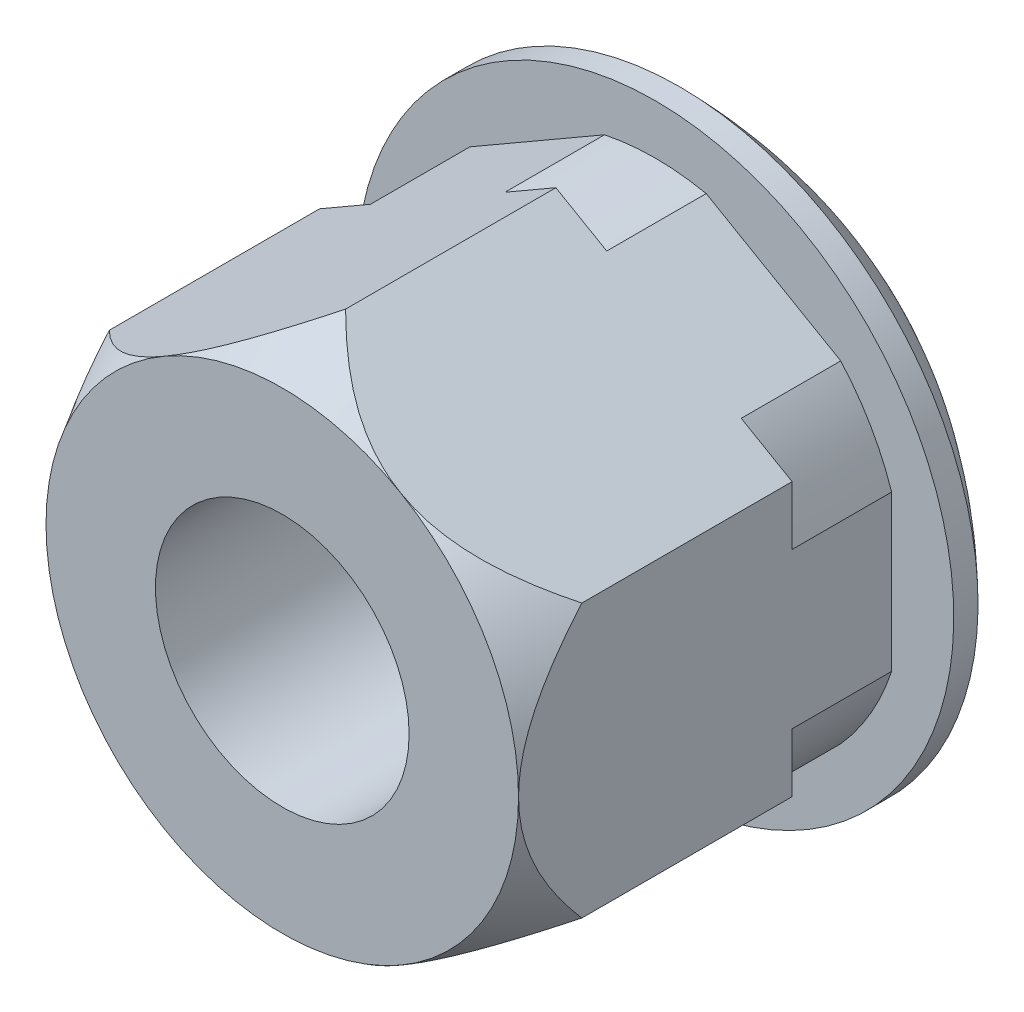
SolidWorks part; units mm, degrees
ref_plane "前视基准面" through (0, 0, 0) normal (0, 0, 1) x (1, 0, 0)
ref_plane "上视基准面" through (0, 0, 0) normal (0, 1, 0) x (1, 0, 0)
ref_plane "右视基准面" through (0, 0, 0) normal (1, 0, 0) x (0, 0, -1)
sketch "草图1" plane through (0, 0, 0) normal (0, 0, 1) x (1, 0, 0)
  line L1 (0, 10.9697) -> (-9.5, 5.4848)
  line L2 (-9.5, 5.4848) -> (-9.5, -5.4848)
  line L3 (-9.5, -5.4848) -> (0, -10.9697)
  line L4 (0, -10.9697) -> (9.5, -5.4848)
  line L5 (9.5, -5.4848) -> (9.5, 5.4848)
  line L6 (9.5, 5.4848) -> (0, 10.9697)
  circle A0 centre (0, 0) radius 9.5 construction
  point P1 (0, 0)
  dimension "D1" = 19
extrude "凸台-拉伸1" add sketch "草图1" against normal blind 15
sketch "草图2" plane through (0, 0, -15) normal (0, 0, -1) x (-1, 0, 0)
  circle A0 centre (0, 0) radius 10
  dimension "D1" = 20
extrude "切除-拉伸1" cut sketch "草图2" against normal blind 4 flip side to cut
sketch "草图3" plane through (0, 0, 0) normal (1, 0, 0) x (0, 0, -1)
  line L0 (15, 0) -> (15, 12)
  line L1 (15, -3.1225) -> (15, 3.1225) construction
  line L2 (15, 12) -> (15.9759, 12)
  line L3 (20, 6.5) -> (20, 0)
  line L4 (8.25, 0) -> (-8.25, 0) construction
  line L5 (20, 0) -> (15, 0) construction
  line L6 (0, 11) -> (0, -11) construction
  line L7 (15, 0) -> (20, 0)
  arc A0 (15.9759, 12) -> (20, 6.5) centre (-2, -5.3743) cw
  point P7 (15.4879, 12)
  point P13 (16.7826, 12)
  dimension "D1" = 25
  dimension "D2" = 24
  dimension "D3" = 13
  dimension "D4" = 20
  dimension "D5" = 5
  dimension "D6" = 2
revolve "旋转1" add sketch "草图3" angle 360 about L5
sketch "草图4" plane through (0, 0, 0) normal (0, 0, 1) x (1, 0, 0)
  circle A0 centre (0, 0) radius 9.5
  dimension "D1" = 19
extrude "切除-拉伸2" cut sketch "草图4" against normal through all draft 30 flip side to cut
hole_wizard "M12 螺纹孔1" positions "草图5" profile "草图7" tap size "M12" standard "GB" end condition up to next
sketch "草图5" plane through (0, 0, 0) normal (0, 0, 1) x (1, 0, 0)
  point P0 (0, 0)
sketch "草图7" plane through (0, 0, 0) normal (1, 0, 0) x (0, -1, 0)
  line L0 (0, 0) -> (0, 20)
  line L1 (0, 20) -> (5.1, 20)
  line L2 (5.1, 20) -> (5.1, 0)
  line L5 (5.1, 0) -> (0, 0)
  line L11 (0, -6.35) -> (0, 107.95) construction
  dimension "通孔螺纹孔钻头直径" = 10.2
  dimension "通孔螺纹孔钻头深度" = 20
cosmetic thread "孔螺纹线1" parameters "D2"=12
